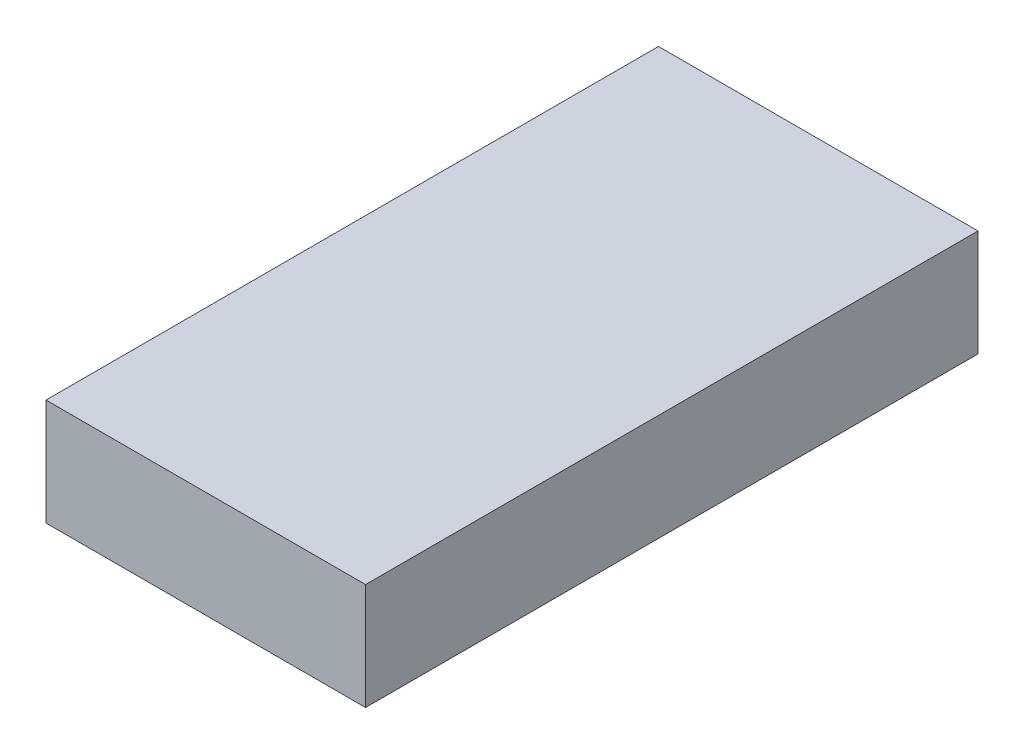
SolidWorks part; units mm, degrees
ref_plane "Front Plane" through (0, 0, 0) normal (0, 0, 1) x (1, 0, 0)
ref_plane "Top Plane" through (0, 0, 0) normal (0, 1, 0) x (1, 0, 0)
ref_plane "Right Plane" through (0, 0, 0) normal (1, 0, 0) x (0, 0, -1)
sketch "Sketch1" plane through (0, 0, 0) normal (0, 1, 0) x (1, 0, 0)
  line L1 (0, 0) -> (60, 0)
  line L2 (0, 0) -> (0, 115)
  line L3 (0, 115) -> (60, 115)
  line L4 (60, 0) -> (60, 115)
  dimension "D1" = 60
  dimension "D2" = 115
extrude "Boss-Extrude1" add sketch "Sketch1" along normal blind 20
